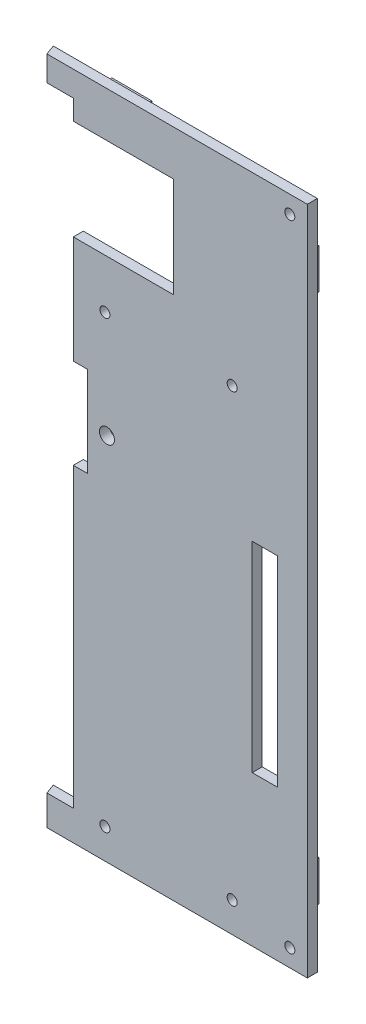
SolidWorks part; units mm, degrees
ref_plane "Front Plane" through (0, 0, 0) normal (0, 0, 1) x (1, 0, 0)
ref_plane "Top Plane" through (0, 0, 0) normal (0, 1, 0) x (1, 0, 0)
ref_plane "Right Plane" through (0, 0, 0) normal (1, 0, 0) x (0, 0, -1)
sketch "Sketch1" plane through (0, 0, 0) normal (0, 0, 1) x (1, 0, 0)
  line L0 (5.0715, -3.5) -> (57.7824, -3.5) construction
  line L1 (5.0715, -3.5) -> (57.7824, -3.5)
  line L2 (57.7824, 130.2602) -> (57.7824, -3.5) construction
  line L3 (57.7824, 130.2602) -> (57.7824, -3.5)
  line L4 (5.0715, 130.2602) -> (57.7824, 130.2602) construction
  line L5 (5.0715, 130.2602) -> (57.7824, 130.2602)
  line L6 (5.0715, -3.5) -> (5.0715, 2.5)
  line L7 (5.0715, 2.5) -> (11.0715, 2.5)
  line L8 (11.0715, 2.5) -> (11.0715, 125.2602)
  line L9 (11.0715, 125.2602) -> (5.0715, 125.2602)
  line L10 (5.0715, 125.2602) -> (5.0715, 130.2602)
  circle A0 centre (54.2824, 0) radius 1 construction
  circle A1 centre (54.2824, 0) radius 1
  circle A2 centre (54.2824, 126.7602) radius 1 construction
  circle A3 centre (54.2824, 126.7602) radius 1
  circle A4 centre (17.7824, 70.2602) radius 1.5 construction
  circle A5 centre (17.7824, 70.2602) radius 1.5
  dimension "D1" = 6
  dimension "D2" = 5
  dimension "D3" = 6
extrude "Boss-Extrude1" add sketch "Sketch1" along normal blind 2
sketch "Sketch2" plane through (0, -3.5, 0) normal (0, -1, 0) x (1, 0, 0)
  line L0 (5.0715, 0) -> (1.1577, -10.7531) construction
  line L1 (6.0364, 2.6511) -> (1.1577, -10.7531)
  line L2 (6.0364, 2.6511) -> (3.5279, 2.3413)
  line L3 (3.5279, 2.3413) -> (1.1577, -10.7531)
extrude "Cut-Extrude1" cut sketch "Sketch2" against normal through all
sketch "Sketch3" plane through (0, 0, 2) normal (0, 0, 1) x (1, 0, 0)
  line L0 (11.0715, 125.2602) -> (11.0715, 2.5) construction
  line L1 (46.7824, 26.5) -> (51.7824, 26.5)
  line L2 (46.7824, 26.5) -> (46.7824, 66.5)
  line L3 (46.7824, 66.5) -> (51.7824, 66.5)
  line L4 (51.7824, 26.5) -> (51.7824, 66.5)
  line L5 (46.7824, 26.5) -> (51.7824, 66.5) construction
  line L6 (46.7824, 66.5) -> (51.7824, 26.5) construction
  line L7 (11.0715, 121.2602) -> (31.0715, 121.2602)
  line L8 (11.0715, 121.2602) -> (11.0715, 101.2602)
  line L9 (11.0715, 101.2602) -> (31.0715, 101.2602)
  line L10 (31.0715, 121.2602) -> (31.0715, 101.2602)
  line L11 (57.7824, 130.2602) -> (5.7994, 130.2602) construction
  line L12 (57.7824, -3.5) -> (57.7824, 130.2602) construction
  line L13 (5.7994, -3.5) -> (57.7824, -3.5) construction
  line L15 (-14.078, 61.7801) -> (13.922, 61.7801)
  line L16 (-14.078, 61.7801) -> (-14.078, 79.7801)
  line L17 (-14.078, 79.7801) -> (13.922, 79.7801)
  line L18 (-14.078, 61.7801) -> (-2.0036, 61.7801)
  line L19 (-2.0036, 61.7801) -> (-2.0036, 72.9801)
  line L20 (-2.0036, 72.9801) -> (-14.078, 72.9801)
  line L21 (-14.078, 72.9801) -> (-14.078, 61.7801)
  line L22 (-14.078, 61.7801) -> (-2.0036, 61.7801) construction
  line L23 (-2.0036, 61.7801) -> (-2.0036, 72.9801) construction
  line L24 (-2.0036, 72.9801) -> (-14.078, 72.9801) construction
  line L25 (-14.078, 72.9801) -> (-14.078, 61.7801) construction
  line L26 (13.922, 61.7801) -> (13.922, 79.7801)
  point P0 (49.2824, 46.5)
  dimension "D1" = 9
  dimension "D2" = 20
  dimension "D3" = 20
  dimension "D4" = 6
  dimension "D5" = 40
  dimension "D6" = 30
  dimension "D7" = 5
  dimension "D9" = 18
  dimension "D10" = 28
  dimension "D8" = 0
extrude "Cut-Extrude2" cut sketch "Sketch3" against normal blind 2
sketch "Sketch4" plane through (0, 0, 2) normal (0, 0, 1) x (1, 0, 0)
  line L0 (5.7994, -3.5) -> (57.7824, -3.5) construction
  line L1 (17.3824, 2.5) -> (42.7824, 2.5) construction
  line L2 (17.3824, 2.5) -> (17.3824, 91.4) construction
  line L3 (17.3824, 91.4) -> (42.7824, 91.4) construction
  line L4 (42.7824, 2.5) -> (42.7824, 91.4) construction
  line L5 (57.7824, -3.5) -> (57.7824, 130.2602) construction
  circle A0 centre (17.3824, 2.5) radius 1
  circle A1 centre (42.7824, 2.5) radius 1
  circle A2 centre (42.7824, 91.4) radius 1
  circle A3 centre (17.3824, 91.4) radius 1
  dimension "D1" = 2
  dimension "D2" = 25.4
  dimension "D3" = 88.9
  dimension "D4" = 6
  dimension "D5" = 15
extrude "Cut-Extrude3" cut sketch "Sketch4" against normal blind 2
sketch "Sketch5" plane through (0, 0, 2) normal (0, 0, 1) x (1, 0, 0)
  line L0 (5.0715, -2) -> (50.7824, -2) construction
  line L1 (5.0715, -2) -> (71.7784, -2) construction
  line L2 (50.7824, 128.7602) -> (2.648, 128.7602) construction
  line L3 (74.9659, 128.7602) -> (2.648, 128.7602) construction
  line L4 (56.2824, 58.5301) -> (56.2824, 3.5) construction
  line L5 (56.2824, 140.7713) -> (56.2824, -11.4419) construction
  line L6 (57.7824, -3.5) -> (57.7824, 130.2602) construction
  line L7 (22.7824, 128.6102) -> (14.7824, 128.6102)
  line L8 (22.7824, 128.6102) -> (22.7824, 127.1102)
  line L9 (22.7824, 127.1102) -> (14.7824, 127.1102)
  line L10 (14.7824, 128.6102) -> (14.7824, 127.1102)
  line L11 (22.7824, -0.35) -> (14.7824, -0.35)
  line L12 (22.7824, -0.35) -> (22.7824, -1.85)
  line L13 (22.7824, -1.85) -> (14.7824, -1.85)
  line L14 (14.7824, -0.35) -> (14.7824, -1.85)
  line L15 (54.6324, 120.2602) -> (56.1324, 120.2602)
  line L16 (54.6324, 120.2602) -> (54.6324, 112.2602)
  line L17 (54.6324, 112.2602) -> (56.1324, 112.2602)
  line L18 (56.1324, 120.2602) -> (56.1324, 112.2602)
  line L19 (54.6324, 14.5) -> (56.1324, 14.5)
  line L20 (54.6324, 14.5) -> (54.6324, 6.5)
  line L21 (54.6324, 6.5) -> (56.1324, 6.5)
  line L22 (56.1324, 14.5) -> (56.1324, 6.5)
  line L23 (5.7994, -3.5) -> (57.7824, -3.5) construction
  line L24 (57.7824, 130.2602) -> (5.7994, 130.2602) construction
  dimension "D1" = 0.15
  dimension "D2" = 0.15
  dimension "D3" = 0.15
  dimension "D4" = 0.15
  dimension "D5" = 8
  dimension "D6" = 8
  dimension "D7" = 8
  dimension "D8" = 8
  dimension "D9" = 35
  dimension "D10" = 1.5
  dimension "D11" = 1.5
  dimension "D12" = 10
  dimension "D13" = 10
  dimension "D14" = 1.5
  dimension "D15" = 1.5
  dimension "D16" = 35
extrude "Boss-Extrude2" add sketch "Sketch5" against normal blind 4
